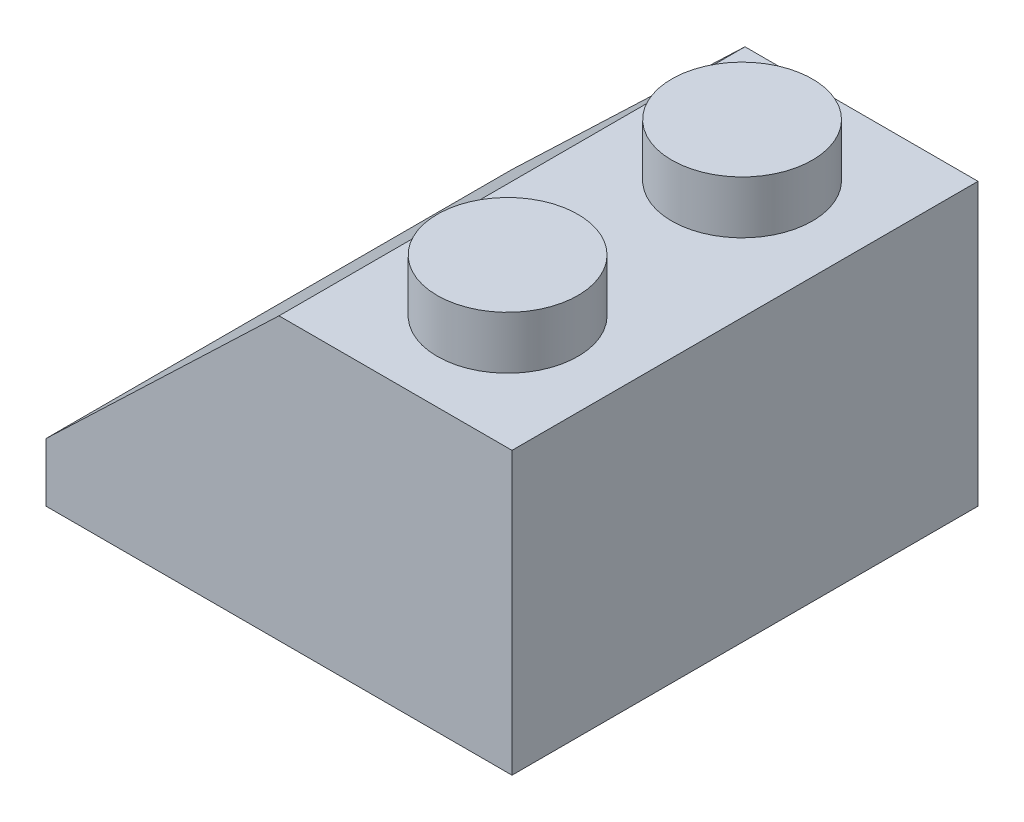
SolidWorks part; units mm, degrees
ref_plane "Front Plane" through (0, 0, 0) normal (0, 0, 1) x (1, 0, 0)
ref_plane "Top Plane" through (0, 0, 0) normal (0, 1, 0) x (1, 0, 0)
ref_plane "Right Plane" through (0, 0, 0) normal (1, 0, 0) x (0, 0, -1)
sketch "Sketch1" plane through (0, 0, 0) normal (0, 0, 1) x (1, 0, 0)
  line L0 (0, 0) -> (-15.9, 0)
  line L1 (-15.9, 0) -> (-15.9, 2)
  line L2 (-15.9, 2) -> (-7.95, 9.6)
  line L3 (-7.95, 9.6) -> (0, 9.6)
  line L4 (0, 9.6) -> (0, 0)
  dimension "D1" = 15.9
  dimension "D2" = 9.6
  dimension "D3" = 2
  dimension "D4" = 7.95
extrude "Boss-Extrude1" add sketch "Sketch1" against normal mid plane 15.9
sketch "Sketch2" plane through (0, 9.6, 0) normal (0, 1, 0) x (1, 0, 0)
  line L0 (-7.95, 7.95) -> (-7.95, -7.95) construction
  line L1 (0, -7.95) -> (-7.95, -7.95) construction
  circle A0 centre (-4.05, -4.05) radius 2.4
  dimension "D1" = 4.8
  dimension "D2" = 3.9
  dimension "D3" = 3.9
extrude "Boss-Extrude2" add sketch "Sketch2" along normal blind 1.8
pattern_linear "LPattern1" count 2 spacing 8 along (0, 0, -1) of "Boss-Extrude2"
shell "Shell1" thickness 0.5
sketch "Sketch3" plane through (0, 9.1, 0) normal (0, -1, 0) x (1, 0, 0)
  line L1 (-4.05, -3.95) -> (-12.05, -3.95) construction
  line L2 (-12.05, -3.95) -> (-4.05, -3.95) construction
  line L3 (-4.05, -3.95) -> (-12.05, -3.95) construction
  line L4 (-12.05, -3.95) -> (-4.05, -3.95) construction
  line L5 (-4.05, 4.05) -> (-12.05, 4.05) construction
  line L6 (-12.05, 4.05) -> (-4.05, -3.95) construction
  line L7 (-12.05, -3.95) -> (-4.05, 4.05) construction
  circle A0 centre (-8.05, 0.05) radius 3
  circle A1 centre (-8.05, 0.05) radius 2.4
  point P1 (-8.05, 0.05)
  dimension "D3" = 6
  dimension "D4" = 4.8
  dimension "D1" = 8
  dimension "D2" = 8
  dimension "D5" = 8
extrude "Boss-Extrude3" add sketch "Sketch3" along normal up to surface (9.1 mm away)
sketch "Sketch4" plane through (-8.5913, 8.9869, 0) normal (-0.691, 0.7228, 0) x (0.7228, 0.691, 0)
  line L4 (-10.1111, -7.95) -> (0.8872, -7.95)
  line L5 (0.8872, -7.95) -> (0.8872, 7.95)
  line L6 (0.8872, 7.95) -> (-10.1111, 7.95)
  line L7 (-10.1111, 7.95) -> (-10.1111, -7.95)
  line L8 (-10.1111, -7.95) -> (0.8872, -7.95)
  line L9 (0.8872, -7.95) -> (0.8872, 7.95)
  line L10 (0.8872, 7.95) -> (-10.1111, 7.95)
  line L11 (-10.1111, 7.95) -> (-10.1111, -7.95)
  dimension "D1" = 0
extrude "Cut-Extrude1" cut sketch "Sketch4" along normal through all
